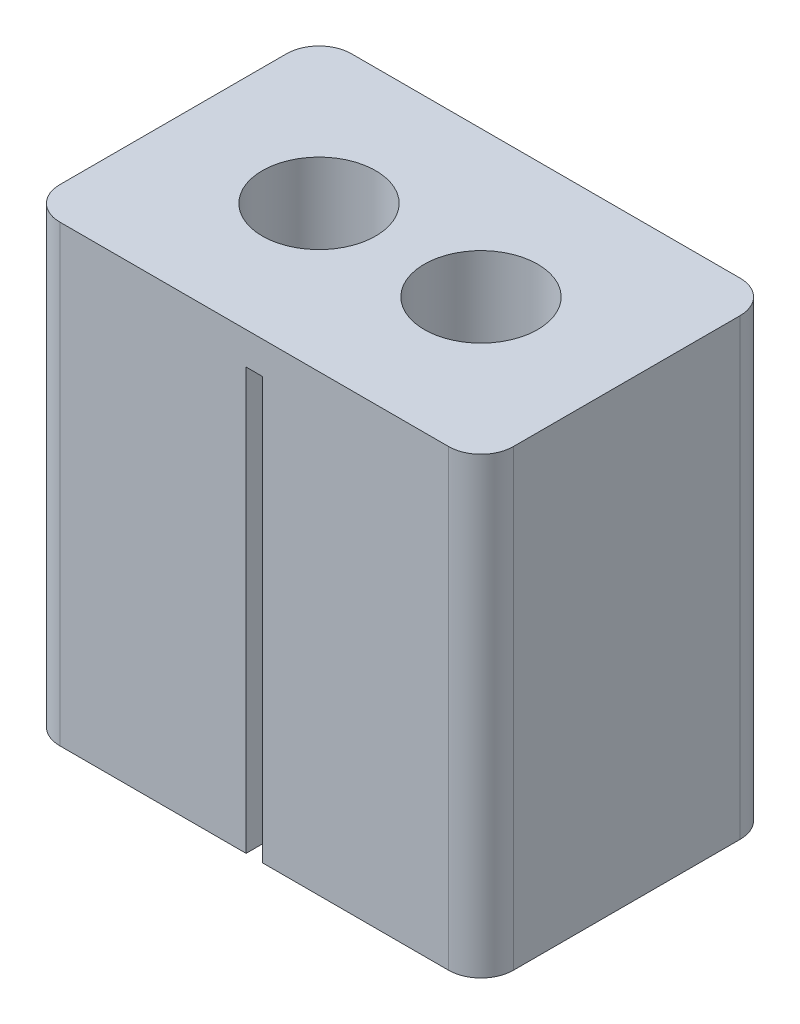
SolidWorks part; units mm, degrees
ref_plane "前视基准面" through (0, 0, 0) normal (0, 0, 1) x (1, 0, 0)
ref_plane "上视基准面" through (0, 0, 0) normal (0, 1, 0) x (1, 0, 0)
ref_plane "右视基准面" through (0, 0, 0) normal (1, 0, 0) x (0, 0, -1)
sketch "草图1" plane through (0, 0, 0) normal (0, 1, 0) x (1, 0, 0)
  line L0 (-7, 4.5) -> (7, -4.5) construction
  line L1 (-7, 4.5) -> (7, 4.5)
  line L2 (-7, 4.5) -> (-7, -4.5)
  line L3 (-7, -4.5) -> (7, -4.5)
  line L4 (7, 4.5) -> (7, -4.5)
  dimension "D1" = 9
  dimension "D2" = 14
extrude "凸台-拉伸1" add sketch "草图1" along normal blind 14
fillet "圆角1" radius 1 4 edges at (-7, 7, -4.5) (7, 7, -4.5) (7, 7, 4.5) (-7, 7, 4.5)
sketch "草图3" plane through (0, 14, 0) normal (0, 1, 0) x (1, 0, 0)
  line L0 (-2.5, 0) -> (2.5, 0) construction
  circle A0 centre (-2.5, 0) radius 1.75
  circle A1 centre (2.5, 0) radius 1.75
  point P2 (0, 0)
  dimension "D2" = 3.5
  dimension "D1" = 5
extrude "切除-拉伸2" cut sketch "草图3" against normal blind 7
sketch "草图4" plane through (0, 7, 0) normal (0, 1, 0) x (1, 0, 0)
  circle A0 centre (-2.5, 0) radius 1.05
  circle A1 centre (-2.5, 0) radius 1.75
  circle A2 centre (-2.5, 0) radius 1.75 construction
  circle A3 centre (2.5, 0) radius 1.75
  circle A4 centre (2.5, 0) radius 1.75 construction
  circle A5 centre (2.5, 0) radius 1.05
  dimension "D3" = 2.1
  dimension "D1" = 0
  dimension "D2" = 0
extrude "切除-拉伸3" cut sketch "草图4" against normal up to next
sketch "草图6" plane through (0, 14, 0) normal (0, 1, 0) x (1, 0, 0)
  line L0 (6, 4.5) -> (-6, 4.5) construction
  line L1 (-0.25, -4.5) -> (0.25, -4.5)
  line L2 (-0.25, -4.5) -> (-0.25, 4.5)
  line L3 (-0.25, 4.5) -> (0.25, 4.5)
  line L4 (0.25, -4.5) -> (0.25, 4.5)
  line L5 (-0.25, -4.5) -> (0.25, 4.5) construction
  line L6 (-0.25, 4.5) -> (0.25, -4.5) construction
  point P0 (0, 0)
  dimension "D1" = 0.5
extrude "切除-拉伸4" cut sketch "草图6" against normal up to next from offset 1
